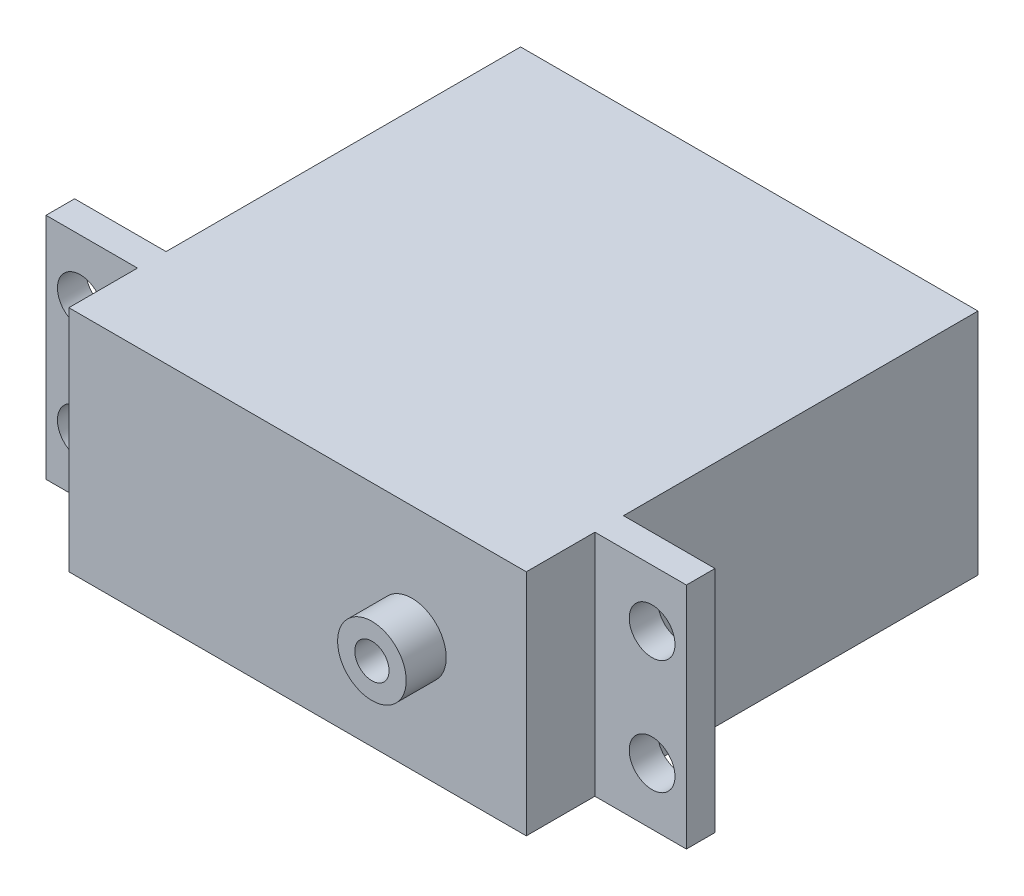
SolidWorks part; units mm, degrees
ref_plane "前视基准面" through (0, 0, 0) normal (0, 0, 1) x (1, 0, 0)
ref_plane "上视基准面" through (0, 0, 0) normal (0, 1, 0) x (1, 0, 0)
ref_plane "右视基准面" through (0, 0, 0) normal (1, 0, 0) x (0, 0, -1)
sketch "草图1" plane through (0, 0, 0) normal (0, 0, 1) x (1, 0, 0)
  line L1 (-20, -10) -> (20, -10)
  line L2 (-20, -10) -> (-20, 10)
  line L3 (-20, 10) -> (20, 10)
  line L4 (20, -10) -> (20, 10)
  line L5 (-20, -10) -> (20, 10) construction
  line L6 (-20, 10) -> (20, -10) construction
  point P0 (0, 0)
  dimension "D1" = 20
  dimension "D2" = 40
extrude "凸台-拉伸1" add sketch "草图1" along normal blind 39.5
sketch "草图2" plane through (0, 0, 39.5) normal (0, 0, 1) x (1, 0, 0)
  line L0 (20, -10) -> (20, 10) construction
  circle A0 centre (10, 0) radius 3
  circle A1 centre (10, 0) radius 1.5
  dimension "D1" = 10
  dimension "D2" = 3
  dimension "D3" = 6
extrude "凸台-拉伸2" add sketch "草图2" along normal blind 3.5
ref_plane "基准面1" through (0, 0, 33.5) normal (0, 0, 1) x (1, 0, 0)
sketch "草图4" plane through (0, 0, 33.5) normal (0, 0, 1) x (1, 0, 0)
  line L1 (-28, -10) -> (28, -10)
  line L2 (-28, -10) -> (-28, 10)
  line L3 (-28, 10) -> (28, 10)
  line L4 (28, -10) -> (28, 10)
  line L5 (-28, -10) -> (28, 10) construction
  line L6 (-28, 10) -> (28, -10) construction
  circle A0 centre (25, 5) radius 2
  circle A1 centre (25, -5) radius 2
  circle A2 centre (-25, 5) radius 2
  circle A3 centre (-25, -5) radius 2
  point P0 (0, 0)
  dimension "D3" = 4
  dimension "D4" = 4
  dimension "D5" = 4
  dimension "D6" = 4
  dimension "D1" = 20
  dimension "D2" = 56
  dimension "D7" = 3
  dimension "D8" = 3
  dimension "D9" = 5
  dimension "D10" = 5
  dimension "D11" = 5
  dimension "D12" = 5
  dimension "D13" = 3
  dimension "D14" = 3
extrude "凸台-拉伸3" add sketch "草图4" against normal blind 2.5
